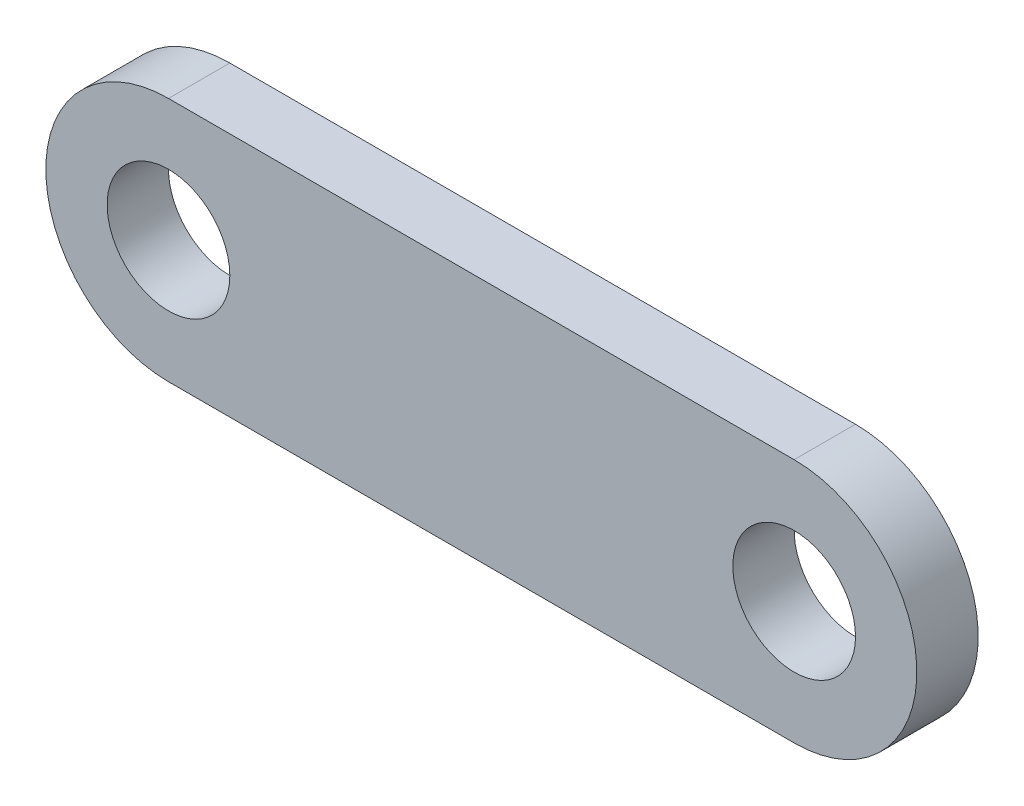
SolidWorks part; units mm, degrees
ref_plane "Alzado" through (0, 0, 0) normal (0, 0, 1) x (1, 0, 0)
ref_plane "Planta" through (0, 0, 0) normal (0, 1, 0) x (1, 0, 0)
ref_plane "Vista lateral" through (0, 0, 0) normal (1, 0, 0) x (0, 0, -1)
sketch "Croquis1" plane through (0, 0, 0) normal (0, 0, 1) x (1, 0, 0)
  line L0 (-25.5, 0) -> (25.5, 0) construction
  line L1 (-25.5, 10) -> (25.5, 10)
  line L2 (-25.5, -10) -> (25.5, -10)
  arc A0 (-25.5, 10) -> (-25.5, -10) centre (-25.5, 0) ccw
  arc A1 (25.5, -10) -> (25.5, 10) centre (25.5, 0) ccw
  circle A2 centre (25.5, 0) radius 5
  circle A3 centre (-25.5, 0) radius 5
  point P2 (0, 0)
  dimension "D2" = 10
  dimension "D1" = 51
  dimension "D3" = 20
extrude "Saliente-Extruir1" add sketch "Croquis1" along normal blind 5
equation "\"largo\"= 51mm"
